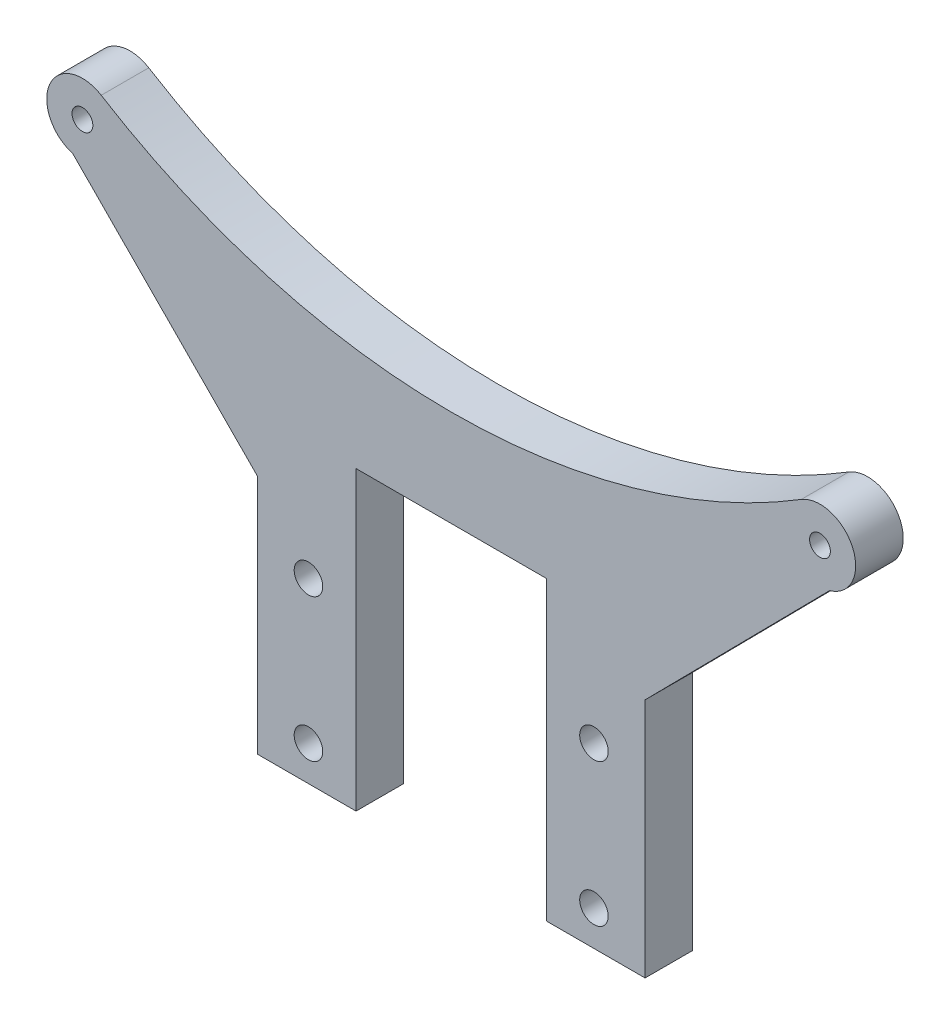
SolidWorks part; units mm, degrees
ref_plane "Front Plane" through (0, 0, 0) normal (0, 0, 1) x (1, 0, 0)
ref_plane "Top Plane" through (0, 0, 0) normal (0, 1, 0) x (1, 0, 0)
ref_plane "Right Plane" through (0, 0, 0) normal (1, 0, 0) x (0, 0, -1)
sketch "Sketch1" plane through (0, 0, 0) normal (0, 0, 1) x (1, 0, 0)
  line L0 (0, 26.8447) -> (0, -57.25) construction
  line L1 (12.7, 0) -> (-12.7, 0)
  line L2 (-12.7, 0) -> (-12.7, -39.5939)
  line L3 (12.7, -39.5939) -> (25.8722, -39.5939)
  line L4 (-49.2125, 26.8447) -> (6.4719, 26.8447) construction
  line L5 (-12.7, -39.5939) -> (-25.8722, -39.5939)
  line L6 (12.7, 0) -> (12.7, -39.5939)
  line L7 (-25.8722, -39.5939) -> (-25.8722, -7.4456)
  line L8 (25.8722, -39.5939) -> (25.8722, -7.4456)
  line L9 (25.8722, -7.4456) -> (50.503, 17.4979)
  line L10 (-25.8722, -7.4456) -> (-50.503, 17.4979)
  circle A0 centre (-19.05, -15.875) radius 1.905
  arc A1 (-46.7103, 26.1344) -> (-50.503, 17.4979) centre (-49.2125, 22.0822) ccw
  arc A2 (46.7103, 26.1344) -> (-46.7103, 26.1344) centre (0, 101.7783) cw
  circle A3 centre (19.05, -15.875) radius 1.905
  circle A4 centre (-49.2125, 22.0822) radius 1.3891
  circle A5 centre (-19.05, -34.925) radius 1.905
  circle A6 centre (19.05, -34.925) radius 1.905
  circle A9 centre (49.2125, 22.0822) radius 1.3891
  arc A10 (46.7103, 26.1344) -> (50.503, 17.4979) centre (49.2125, 22.0822) cw
  point P9 (-49.2125, 22.0822)
  point P14 (0, 12.8747)
  point P28 (0, 0)
  dimension "D4" = 19.05
  dimension "D7" = 9.525
  dimension "D9" = 50.503
  dimension "D12" = 2.7781
  dimension "D13" = 3.81
  dimension "D14" = 15.875
  dimension "D5" = 88.9036
  dimension "D3" = 19.05
  dimension "D1" = 12.7
  dimension "D8" = 13.97
extrude "Boss-Extrude1" add sketch "Sketch1" along normal blind 6.35
